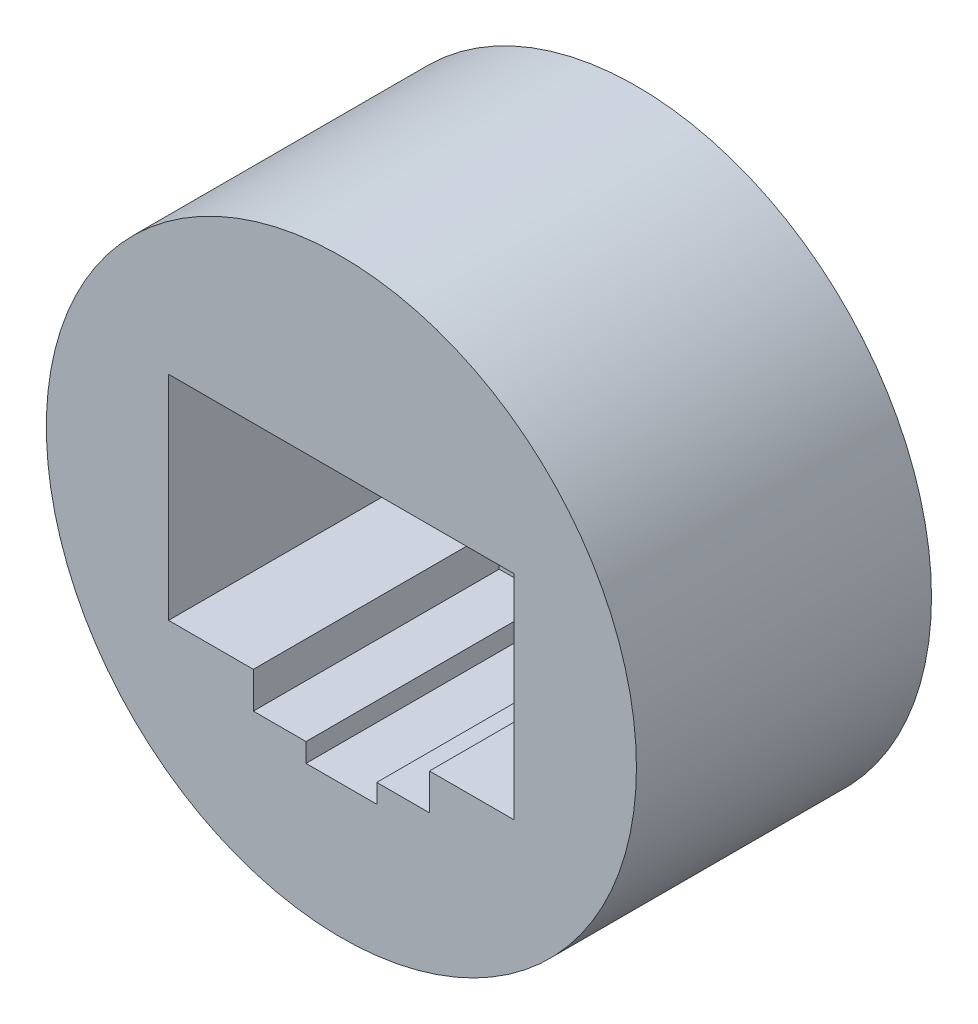
SolidWorks part; units mm, degrees
ref_plane "Front Plane" through (0, 0, 0) normal (0, 0, 1) x (1, 0, 0)
ref_plane "Top Plane" through (0, 0, 0) normal (0, 1, 0) x (1, 0, 0)
ref_plane "Right Plane" through (0, 0, 0) normal (1, 0, 0) x (0, 0, -1)
sketch "Sketch2" plane through (0, 0, 0) normal (0, 0, 1) x (1, 0, 0)
  circle A0 centre (0, 0) radius 12
  dimension "D1" = 24
extrude "Boss-Extrude1" add sketch "Sketch2" along normal blind 12
sketch "Sketch3" plane through (0, 0, 12) normal (0, 0, 1) x (1, 0, 0)
  line L0 (3.581, -4.3343) -> (7.0286, -4.3343)
  line L1 (-7.0286, 4.3343) -> (7.0286, 4.3343)
  line L2 (-7.0286, 4.3343) -> (-7.0286, -4.3343)
  line L3 (-7.0286, -4.3343) -> (-3.581, -4.3343)
  line L4 (7.0286, 4.3343) -> (7.0286, -4.3343)
  line L5 (-7.0286, 4.3343) -> (7.0286, -4.3343) construction
  line L6 (-7.0286, -4.3343) -> (7.0286, 4.3343) construction
  line L8 (-3.581, -4.3343) -> (-3.581, -5.8071)
  line L9 (-3.581, -5.8071) -> (-1.4392, -5.8071)
  line L10 (3.581, -4.3343) -> (3.581, -5.8071)
  line L11 (-3.581, -2.8615) -> (3.581, -5.8071) construction
  line L12 (-3.581, -5.8071) -> (3.581, -2.8615) construction
  line L14 (-1.4392, -5.8071) -> (-1.4392, -6.5768)
  line L15 (-1.4392, -6.5768) -> (1.4392, -6.5768)
  line L16 (1.4392, -5.8071) -> (1.4392, -6.5768)
  line L17 (-1.4392, -5.0374) -> (1.4392, -6.5768) construction
  line L18 (-1.4392, -6.5768) -> (1.4392, -5.0374) construction
  line L19 (1.4392, -5.8071) -> (3.581, -5.8071)
  point P0 (0, 0)
  point P6 (0, -4.3343)
  point P11 (0, -5.8071)
extrude "Cut-Extrude1" cut sketch "Sketch3" against normal blind 10
